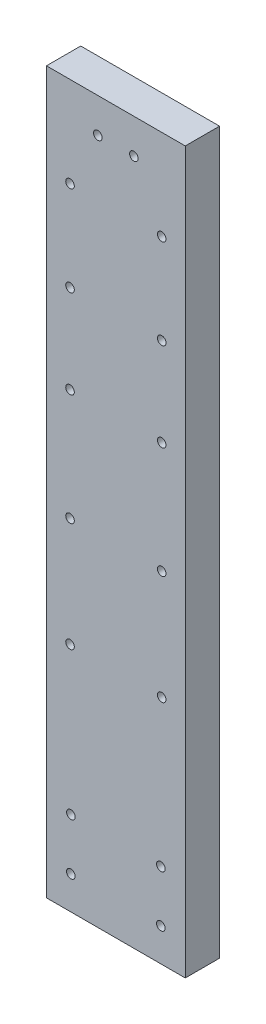
SolidWorks part; units mm, degrees
ref_plane "Front Plane" through (0, 0, 0) normal (0, 0, 1) x (1, 0, 0)
ref_plane "Top Plane" through (0, 0, 0) normal (0, 1, 0) x (1, 0, 0)
ref_plane "Right Plane" through (0, 0, 0) normal (1, 0, 0) x (0, 0, -1)
sketch "Sketch1" plane through (0, 0, 0) normal (0, 0, 1) x (1, 0, 0)
  line L0 (0, 0) -> (0, 84.1)
  line L1 (16.2, 0) -> (16.2, 84.1)
  line L3 (0, 0) -> (16.2, 0)
  line L6 (16.2, 84.1) -> (0, 84.1)
  circle A0 centre (13.45, 39.74) radius 0.5
  circle A1 centre (2.75, 63.065) radius 0.5
  circle A2 centre (13.45, 52.74) radius 0.5
  circle A3 centre (13.45, 73.565) radius 0.5
  circle A4 centre (2.75, 27) radius 0.5
  circle A5 centre (2.75, 73.565) radius 0.5
  circle A6 centre (2.75, 52.74) radius 0.5
  circle A7 centre (2.85, 9.8464) radius 0.5
  circle A8 centre (13.35, 9.8464) radius 0.5
  circle A9 centre (13.35, 3.8464) radius 0.5
  circle A10 centre (2.85, 3.8464) radius 0.5
  circle A11 centre (6, 80.065) radius 0.5
  circle A12 centre (13.45, 27) radius 0.5
  circle A13 centre (13.45, 63.065) radius 0.5
  circle A14 centre (10.2, 80.065) radius 0.5
  circle A15 centre (2.75, 39.74) radius 0.5
  dimension "D1" = 84.1
  dimension "D2" = 3.8464
extrude "Boss-Extrude1" add sketch "Sketch1" along normal blind 4
